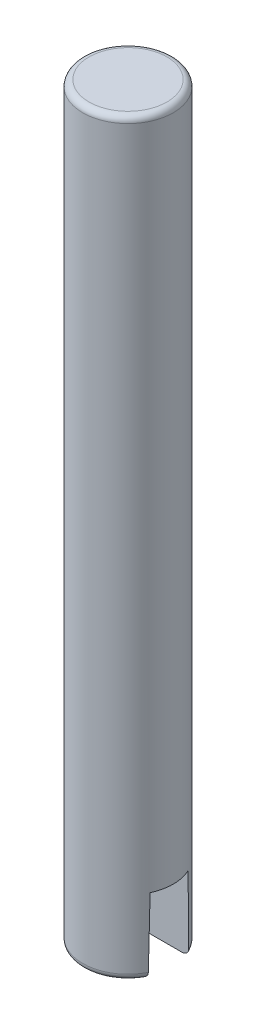
SolidWorks part; units mm, degrees
ref_plane "Front Plane" through (0, 0, 0) normal (0, 0, 1) x (1, 0, 0)
ref_plane "Top Plane" through (0, 0, 0) normal (0, 1, 0) x (1, 0, 0)
ref_plane "Right Plane" through (0, 0, 0) normal (1, 0, 0) x (0, 0, -1)
sketch "Sketch1" plane through (0, 0, 0) normal (0, 1, 0) x (1, 0, 0)
  circle A0 centre (0, 0) radius 3.625
  dimension "D1" = 7.25
extrude "Boss-Extrude1" add sketch "Sketch1" along normal blind 60
sketch "Sketch3" plane through (0, 0, 0) normal (0, -1, 0) x (-1, 0, 0)
  line L0 (5, 0) -> (-5, 0) construction
  line L1 (5, 1.625) -> (-5, 1.625)
  line L2 (5, 1.625) -> (5, -1.625)
  line L3 (5, -1.625) -> (-5, -1.625)
  line L4 (-5, 1.625) -> (-5, -1.625)
  line L5 (0, 1.625) -> (0, -1.625) construction
  point P8 (0, 0)
  dimension "D1" = 3.25
  dimension "D2" = 10
extrude "Cut-Extrude2" cut sketch "Sketch3" against normal blind 6 draft 1
fillet "Fillet2" radius 0.5 3 edges at (0, 60, 3.625) (0, 0, 3.625) (0, 0, -3.625)
sketch "Sketch4" plane through (0, 6, 0) normal (0, -1, 0) x (1, 0, 0)
  line L0 (-3.625, 0) -> (3.625, 0) construction
  line L1 (0, 1.5203) -> (0, -1.5203) construction
  line L2 (3.2908, 1.5203) -> (-3.2908, 1.5203) construction
  line L3 (-3.2908, -1.5203) -> (3.2908, -1.5203) construction
  arc A0 (3.2908, -1.5203) -> (3.2908, 1.5203) centre (0, 0) ccw construction
  arc A1 (-3.2908, 1.5203) -> (-3.2908, -1.5203) centre (0, 0) ccw construction
  point P5 (0, 0)
equation "\"D1@Boss-Extrude1\"=60"
equation "\"D1@Sketch1\"=\"rod diameter@scotch-yoke - assembly.Assembly\""
equation "\"circle diameter\"= 42mm"
equation "\"fillet rad\"= 2.5 * 2mm"
equation "\"carriage length\"= 100mm"
equation "\"carriage width\"= 15mm"
equation "\"carriage height\"= 30mm"
equation "\"rod diameter\"= 7.25mm"
equation "\"bracket width\"= 9mm"
equation "\"yoke width\"= 7mm"
equation "\"yoke height\"= 3mm"
equation "\"D1@Sketch1@scotch-yoke carriage<1>.Part\" = \"carriage length\""
equation "\"D1@Boss-Extrude1@scotch-yoke yoke<1>.Part\" = \"yoke height\""
equation "\"D1@Sketch3\"=\"yoke height@scotch-yoke - assembly.Assembly\"+0.25"
equation "\"D1@Cut-Extrude2\"=\"yoke width@scotch-yoke - assembly.Assembly\"-1"
